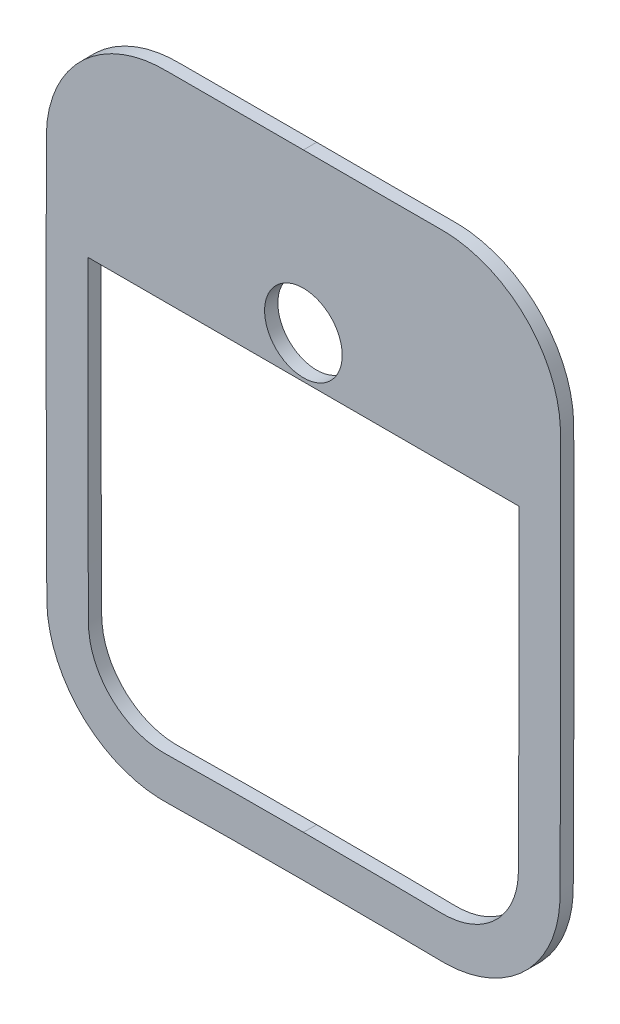
SolidWorks part; units mm, degrees
material "Фанера"
ref_plane "Front Plane" through (0, 0, 0) normal (0, 0, 1) x (1, 0, 0)
ref_plane "Top Plane" through (0, 0, 0) normal (0, 1, 0) x (1, 0, 0)
ref_plane "Right Plane" through (0, 0, 0) normal (1, 0, 0) x (0, 0, -1)
sketch "Эскиз1" plane through (0, 0, 0) normal (0, 0, 1) x (1, 0, 0)
  line L0 (-45.5525, 94.7173) -> (45.5525, 94.7173)
  circle A1 centre (0, 103.6369) radius 5.3081 construction
  circle A2 centre (0, 103.6369) radius 8.2
  spline S2 degree 3 poles (0, 136.3323) (-0.926, 136.3291) (-3.2181, 136.321) (-6.3536, 136.3135) (-10.0117, 136.3073) (-13.7909, 136.3041) (-17.5317, 136.3045) (-20.517, 136.3069) (-22.7788, 136.3098) (-25.0708, 136.3135) (-27.0632, 136.3183) (-28.6511, 136.321) (-29.7284, 136.3268) (-30.7014, 136.287) (-31.5678, 136.22) (-32.3263, 136.1358) (-32.9764, 136.0445) (-33.5181, 135.9548) (-33.9518, 135.874) (-35.3446, 135.5913) (-37.6588, 134.9305) (-40.8493, 133.5098) (-43.8067, 131.6477) (-46.4628, 129.3729) (-48.6957, 126.8267) (-50.5628, 123.9866) (-52.0027, 120.9241) (-52.8229, 118.2255) (-53.2529, 116.0075) (-53.4161, 114.6374) (-53.4855, 113.5584) (-53.5103, 112.8733) (-53.5123, 112.1899) (-53.5144, 111.5078) (-53.5177, 110.3418) (-53.5224, 108.6433) (-53.5285, 106.3641) (-53.5352, 103.6299) (-53.5421, 100.5428) (-53.551, 95.9526) (-53.5594, 90.2813) (-53.5665, 81.1643) (-53.5635, 72.0393) (-53.5483, 62.9223) (-53.5313, 56.0799) (-53.5094, 49.2817) (-53.4858, 43.223) (-53.4628, 37.929) (-53.4409, 33.3706) (-53.4257, 30.1172) (-53.4145, 28.1293) (-53.4127, 27.3671) (-53.3748, 26.4267) (-53.2662, 25.119) (-53.0469, 23.6256) (-52.5487, 21.3707) (-51.6585, 18.7152) (-50.1032, 15.6337) (-48.1548, 12.8477) (-45.7999, 10.3405) (-43.1315, 8.21) (-40.1476, 6.4614) (-36.9729, 5.1716) (-34.2567, 4.4974) (-32.0367, 4.1806) (-30.6305, 4.0789) (-29.4504, 4.0585) (-28.6078, 4.0735) (-27.7675, 4.0844) (-26.411, 4.1036) (-24.587, 4.1279) (-22.3428, 4.1557) (-19.801, 4.1842) (-16.8572, 4.2126) (-13.465, 4.2391) (-10.0714, 4.2595) (-6.7896, 4.2724) (-3.4499, 4.2787) (-1.206, 4.2778) (0, 4.2773) knots 0 0 0 0 0.012711 0.031463 0.04304 0.062926 0.083339 0.094389 0.103905 0.114385 0.125852 0.131253 0.136182 0.140638 0.144615 0.148108 0.151113 0.153626 0.155645 0.157167 0.173136 0.188548 0.204966 0.220928 0.236386 0.2513 0.267442 0.282668 0.289878 0.298437 0.301584 0.30472 0.307845 0.310965 0.314083 0.32385 0.33428 0.345369 0.361382 0.376656 0.408378 0.43923 0.501803 0.533634 0.564377 0.595727 0.626951 0.647544 0.668397 0.689525 0.692203 0.695685 0.699986 0.705119 0.713692 0.720679 0.736803 0.75198 0.767915 0.7833 0.799042 0.814622 0.830614 0.845914 0.852903 0.86138 0.865246 0.869101 0.872946 0.876782 0.887723 0.897987 0.907591 0.922615 0.938396 0.954157 0.969199 0.983445 1 1 1 1 construction
  spline S3 degree 3 poles (0, 4.2773) (1.2324, 4.2778) (3.5235, 4.2786) (6.932, 4.272) (10.2817, 4.2584) (13.748, 4.2372) (17.2125, 4.2095) (20.1567, 4.1805) (22.6884, 4.1514) (24.9793, 4.1227) (26.8446, 4.0975) (28.1752, 4.079) (28.8595, 4.0694) (29.5453, 4.06) (30.2327, 4.0729) (31.0758, 4.1113) (32.0666, 4.1943) (33.1942, 4.3428) (35.0385, 4.6741) (37.6079, 5.3879) (40.7475, 6.7677) (43.6813, 8.5992) (46.2906, 10.8054) (48.579, 13.3853) (50.4521, 16.235) (51.9199, 19.369) (52.7195, 22.0113) (53.1584, 24.2873) (53.3198, 25.6431) (53.3879, 26.7462) (53.4102, 27.3664) (53.414, 27.9508) (53.4167, 28.4997) (53.4193, 29.0136) (53.4268, 30.4953) (53.4391, 32.9452) (53.4554, 36.364) (53.4707, 39.7504) (53.4899, 44.2581) (53.5116, 49.9136) (53.533, 56.6796) (53.5494, 63.4934) (53.5639, 72.568) (53.5664, 81.647) (53.5588, 90.7216) (53.5498, 96.6585) (53.5394, 101.8739) (53.5283, 106.4112) (53.5201, 109.8311) (53.5124, 112.0222) (53.5121, 112.8713) (53.4785, 113.7227) (53.3935, 114.8584) (53.2098, 116.2728) (52.7605, 118.4716) (51.8996, 121.1828) (50.4394, 124.2013) (48.5645, 126.9948) (46.3311, 129.5) (43.6822, 131.737) (40.738, 133.5676) (37.5661, 134.9626) (35.2704, 135.6096) (33.8926, 135.8854) (33.4671, 135.9637) (32.9312, 136.0514) (32.2845, 136.141) (31.5271, 136.2238) (30.6595, 136.2895) (29.683, 136.3275) (28.5999, 136.3206) (27.3351, 136.3188) (25.9489, 136.3154) (24.5019, 136.3127) (23.1303, 136.3104) (21.833, 136.3086) (20.1935, 136.3067) (17.4984, 136.3045) (13.7701, 136.3041) (9.9949, 136.3074) (6.3456, 136.3135) (3.2123, 136.3211) (0.9251, 136.3291) (0, 136.3323) knots 0 0 0 0 0.016917 0.031449 0.046787 0.062897 0.079031 0.094346 0.103313 0.113785 0.125795 0.12892 0.132051 0.135189 0.138334 0.141487 0.146773 0.151975 0.157093 0.172489 0.188447 0.204004 0.219803 0.235185 0.251187 0.266441 0.282542 0.288925 0.298248 0.301256 0.304094 0.306766 0.309277 0.311629 0.313821 0.329617 0.345258 0.36075 0.376101 0.407134 0.438383 0.468976 0.500665 0.562947 0.593601 0.625229 0.644442 0.66519 0.687511 0.691386 0.695268 0.699165 0.703079 0.710899 0.718723 0.733862 0.749811 0.764586 0.779905 0.795731 0.812016 0.82732 0.843155 0.844628 0.846608 0.849094 0.852082 0.855569 0.859551 0.864022 0.868978 0.874416 0.881385 0.888005 0.894279 0.900214 0.905812 0.916784 0.937208 0.95699 0.968604 0.987302 1 1 1 1 construction
  spline S4 degree 1 poles (0, 12.2773) (0, 128.3323) knots 0 0 1 1 construction
  spline S5 degree 1 poles (0, 128.3323) (0, 12.2773) knots 0 0 1 1 construction
  spline S6 degree 3 poles (0, 12.2773) (2.2852, 12.2782) (6.853, 12.2768) (12.5748, 12.2465) (17.145, 12.2104) (20.5757, 12.177) (23.4333, 12.1431) (25.717, 12.1134) (27.141, 12.0942) (28.1419, 12.0802) (28.7075, 12.0724) (29.1448, 12.066) (29.4767, 12.0627) (29.8171, 12.0657) (30.5218, 12.0898) (31.4524, 12.1723) (32.9607, 12.4112) (34.7966, 12.909) (37.5914, 14.1126) (40.7006, 16.3372) (43.0508, 19.3512) (44.3622, 22.084) (44.9299, 23.8954) (45.1872, 25.1913) (45.2945, 25.9399) (45.3547, 26.5044) (45.3879, 26.9723) (45.4051, 27.3642) (45.4132, 27.6833) (45.4158, 28.395) (45.422, 29.5349) (45.429, 30.9559) (45.4375, 32.6626) (45.4458, 34.3688) (45.4565, 36.6438) (45.4695, 39.4874) (45.489, 44.037) (45.5109, 49.7234) (45.5326, 56.5464) (45.5492, 63.3689) (45.5601, 70.1908) (45.5651, 77.0127) (45.5646, 83.8353) (45.5599, 89.4525) (45.5547, 93.3643) (45.5511, 95.6389) (45.5471, 97.9822) (45.5414, 100.8941) (45.5348, 103.7369) (45.5292, 106.0131) (45.5251, 107.7202) (45.5207, 109.425) (45.5169, 110.7017) (45.5139, 111.5529) (45.5127, 111.9972) (45.5122, 112.4102) (45.509, 112.7123) (45.5013, 112.9755) (45.4831, 113.3557) (45.4338, 114.0159) (45.3133, 114.9471) (45.0123, 116.424) (44.4362, 118.2284) (43.1084, 120.9575) (40.7364, 123.9723) (37.5988, 126.2123) (34.7873, 127.4329) (32.931, 127.9452) (31.4232, 128.1964) (30.4592, 128.2877) (29.7017, 128.3215) (29.1225, 128.3246) (28.2046, 128.3197) (27.3601, 128.3188) (26.5088, 128.3167) (25.3666, 128.3142) (23.3728, 128.3107) (20.5226, 128.3067) (17.1028, 128.3043) (12.5424, 128.3045) (6.841, 128.3108) (2.2804, 128.3243) (0, 128.3323) knots 0.000014 0.000014 0.000014 0.000014 0.03126 0.062505 0.078128 0.093751 0.109373 0.117185 0.124996 0.128902 0.130855 0.132808 0.13476 0.136713 0.140619 0.14843 0.156242 0.171865 0.187487 0.218733 0.249978 0.265601 0.281224 0.289035 0.292941 0.296847 0.300752 0.302705 0.304658 0.308564 0.31247 0.320281 0.328092 0.335904 0.343715 0.359338 0.374961 0.406206 0.437452 0.468697 0.499943 0.531188 0.562434 0.593679 0.60836 0.616171 0.624925 0.640548 0.656171 0.663982 0.671793 0.679605 0.687416 0.689369 0.691322 0.693275 0.695227 0.69718 0.699133 0.703039 0.71085 0.718662 0.734284 0.749907 0.781153 0.812398 0.828021 0.843644 0.851455 0.859267 0.863172 0.867078 0.870984 0.874889 0.878795 0.882701 0.890512 0.906135 0.921758 0.937381 0.968626 0.999872 0.999872 0.999872 0.999872
  spline S7 degree 3 poles (0, 128.3323) (-2.2804, 128.3243) (-6.841, 128.3108) (-12.5425, 128.3045) (-17.1025, 128.3043) (-20.5233, 128.3067) (-23.3707, 128.3105) (-25.3689, 128.3143) (-26.5067, 128.3168) (-27.361, 128.3188) (-28.2039, 128.3199) (-29.1199, 128.3242) (-29.7067, 128.3215) (-30.2658, 128.2963) (-30.8496, 128.2512) (-31.6087, 128.165) (-32.933, 127.9452) (-34.7867, 127.4329) (-37.5989, 126.2125) (-40.7365, 123.972) (-43.1082, 120.9578) (-44.4364, 118.228) (-45.0124, 116.4234) (-45.3131, 114.9481) (-45.4341, 114.0121) (-45.4829, 113.3594) (-45.5014, 112.971) (-45.509, 112.7166) (-45.5119, 112.4157) (-45.5132, 111.8386) (-45.5163, 110.8487) (-45.5202, 109.4237) (-45.5249, 107.7184) (-45.5293, 106.012) (-45.5349, 103.7373) (-45.5413, 100.8938) (-45.5471, 97.9819) (-45.5511, 95.6388) (-45.5547, 93.3642) (-45.5599, 89.4524) (-45.5646, 83.8351) (-45.5651, 77.0126) (-45.5601, 70.1906) (-45.5492, 63.3688) (-45.5326, 56.5463) (-45.511, 49.7234) (-45.4889, 44.0369) (-45.4695, 39.4873) (-45.4565, 36.6443) (-45.4456, 34.3687) (-45.4376, 32.6607) (-45.4293, 30.9563) (-45.4224, 29.533) (-45.4163, 28.5465) (-45.4143, 27.9496) (-45.4116, 27.6194) (-45.4048, 27.357) (-45.3882, 26.9775) (-45.3545, 26.5029) (-45.2945, 25.9398) (-45.1873, 25.1913) (-44.93, 23.8962) (-44.3618, 22.0832) (-43.0515, 19.3521) (-40.6999, 16.3366) (-37.5924, 14.1133) (-34.7969, 12.909) (-32.9586, 12.4111) (-31.4575, 12.1727) (-30.5092, 12.0895) (-29.7304, 12.0623) (-29.1932, 12.0635) (-28.2635, 12.0793) (-27.4345, 12.0897) (-26.5722, 12.1021) (-25.4314, 12.1173) (-23.4326, 12.1432) (-20.5754, 12.1769) (-17.1451, 12.2104) (-12.5745, 12.2465) (-6.8531, 12.2768) (-2.2851, 12.2782) (0, 12.2773) knots 0.000128 0.000128 0.000128 0.000128 0.031374 0.062619 0.078242 0.093865 0.109488 0.117299 0.121205 0.125111 0.129016 0.132922 0.136828 0.140733 0.144639 0.148545 0.156356 0.171979 0.187602 0.218847 0.250093 0.265716 0.281338 0.28915 0.296961 0.300867 0.30282 0.304773 0.306725 0.308678 0.312584 0.320395 0.328207 0.336018 0.343829 0.359452 0.375075 0.383827 0.391639 0.406321 0.437566 0.468812 0.500057 0.531303 0.562548 0.593794 0.625039 0.640662 0.656285 0.664096 0.671908 0.679719 0.68753 0.691436 0.693389 0.695342 0.697295 0.699248 0.703153 0.707059 0.710965 0.718776 0.734399 0.750022 0.781267 0.812513 0.828135 0.843758 0.85157 0.859381 0.863287 0.867192 0.871098 0.875004 0.878909 0.882815 0.890627 0.906249 0.921872 0.937495 0.96874 0.999986 0.999986 0.999986 0.999986
  spline S8 degree 1 poles (0, 3.4773) (0, 137.1323) knots 0 0 1 1 construction
  spline S9 degree 1 poles (0, 137.1323) (0, 3.4773) knots 0 0 1 1 construction
  spline S10 degree 3 poles (0, 3.4773) (2.2757, 3.4782) (6.8276, 3.477) (13.6531, 3.4403) (19.344, 3.3919) (23.8909, 3.3354) (26.7457, 3.3039) (29.0013, 3.2589) (31.3686, 3.2808) (34.2865, 3.6489) (37.7068, 4.5715) (42.0422, 6.4407) (46.88, 9.9013) (50.5376, 14.5938) (52.5795, 18.8502) (53.6372, 22.235) (54.111, 25.1353) (54.2253, 27.5102) (54.2154, 29.7782) (54.2401, 32.6283) (54.2578, 37.1801) (54.2851, 42.8727) (54.3108, 49.7028) (54.3399, 58.8101) (54.3631, 70.1942) (54.3666, 81.5785) (54.3587, 90.6857) (54.3492, 97.5161) (54.3345, 103.208) (54.3281, 107.7616) (54.3088, 110.6067) (54.3244, 112.8866) (54.1941, 115.2577) (53.705, 118.158) (52.6247, 121.5345) (50.5543, 125.7781) (46.8715, 130.4456) (42.0298, 133.8934) (37.7006, 135.7677) (34.2865, 136.7034) (31.3719, 137.091) (29.0087, 137.1302) (26.7538, 137.1127) (23.8976, 137.1128) (19.3493, 137.1043) (13.6566, 137.1035) (6.8288, 137.1107) (2.2762, 137.1243) (0, 137.1323) knots -0.000001 -0.000001 -0.000001 -0.000001 0.031249 0.062499 0.09375 0.109375 0.125 0.132813 0.140626 0.156251 0.171876 0.187501 0.218752 0.250002 0.265627 0.281253 0.296878 0.30469 0.312503 0.328128 0.343753 0.375004 0.406254 0.437505 0.500006 0.562507 0.593757 0.625007 0.656258 0.671883 0.687508 0.695321 0.703134 0.718759 0.734384 0.750009 0.78126 0.81251 0.828135 0.843761 0.859386 0.867198 0.875011 0.890636 0.906262 0.937512 0.968762 1.000013 1.000013 1.000013 1.000013
  spline S11 degree 3 poles (0, 137.1323) (-2.2762, 137.1243) (-6.8287, 137.1107) (-13.6566, 137.1035) (-19.3492, 137.1044) (-23.8976, 137.1126) (-26.7535, 137.1129) (-29.0087, 137.1299) (-31.3719, 137.0913) (-34.2864, 136.7033) (-37.7004, 135.7678) (-42.0298, 133.8935) (-46.8714, 130.4457) (-50.5543, 125.778) (-52.6246, 121.5346) (-53.7051, 118.1576) (-54.1942, 115.2577) (-54.3244, 112.886) (-54.3089, 110.6059) (-54.3276, 107.7616) (-54.3349, 103.2075) (-54.349, 97.5159) (-54.3587, 90.6855) (-54.3666, 81.5783) (-54.3631, 70.1941) (-54.3399, 58.81) (-54.3108, 49.7027) (-54.2851, 42.8728) (-54.2576, 37.1799) (-54.2403, 32.6285) (-54.2155, 29.7784) (-54.2255, 27.5093) (-54.1108, 25.1358) (-53.6373, 22.2349) (-52.5798, 18.8513) (-50.538, 14.5939) (-46.8805, 9.9022) (-42.0427, 6.4409) (-37.7078, 4.5721) (-34.2868, 3.6487) (-31.3691, 3.2814) (-29.001, 3.2579) (-26.7453, 3.3042) (-23.891, 3.3355) (-19.3439, 3.3917) (-13.6531, 3.4403) (-6.8275, 3.4769) (-2.2757, 3.4782) (0, 3.4773) knots -0.000013 -0.000013 -0.000013 -0.000013 0.031238 0.062488 0.093738 0.109364 0.124989 0.132802 0.140614 0.156239 0.171865 0.18749 0.21874 0.249991 0.265616 0.281241 0.296866 0.304679 0.312492 0.328117 0.343742 0.374993 0.406243 0.437493 0.499994 0.562495 0.593746 0.624996 0.656247 0.671872 0.687497 0.69531 0.703122 0.718747 0.734373 0.749998 0.781248 0.812499 0.828124 0.843749 0.859374 0.867187 0.875 0.890625 0.90625 0.937501 0.968751 1.000001 1.000001 1.000001 1.000001
  dimension "D3" = 16.4
  dimension "D1" = 8
  dimension "D2" = 0.8
extrude "Бобышка-Вытянуть1" add sketch "Эскиз1" along normal mid plane 2.8 contours S6 S7 L0 A2 | S10 S11 S7 S6
